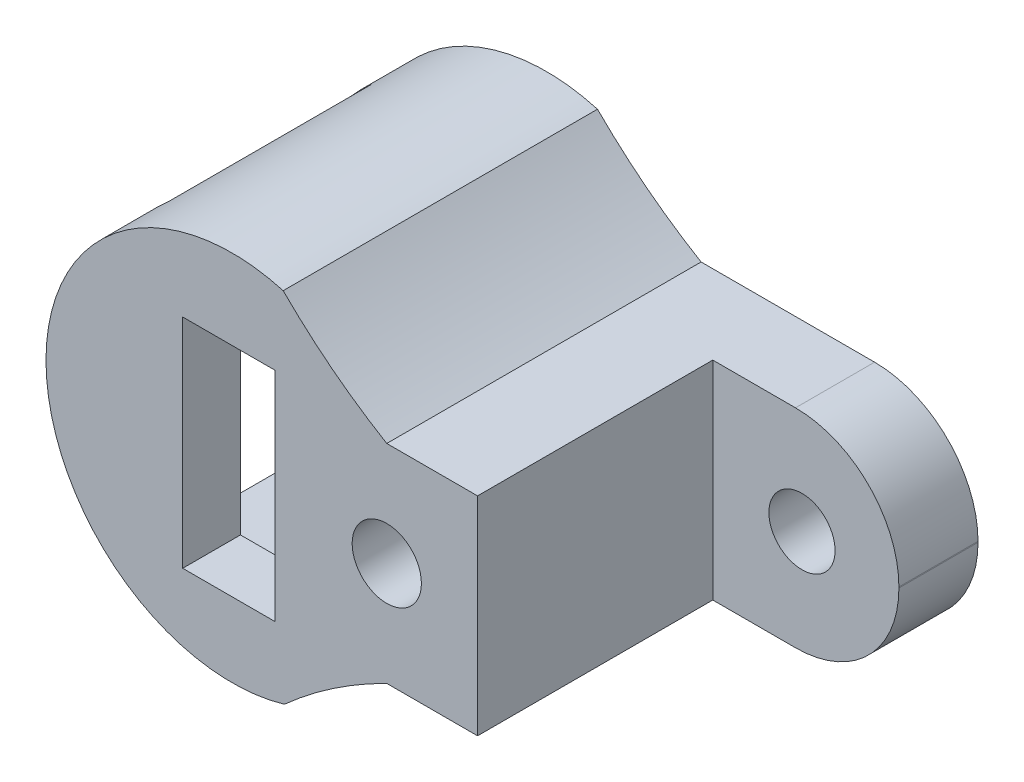
SolidWorks part; units mm, degrees
ref_plane "前视基准面" through (0, 0, 0) normal (0, 0, 1) x (1, 0, 0)
ref_plane "上视基准面" through (0, 0, 0) normal (0, 1, 0) x (1, 0, 0)
ref_plane "右视基准面" through (0, 0, 0) normal (1, 0, 0) x (0, 0, -1)
sketch "草图1" plane through (0, 0, 0) normal (0, 0, 1) x (1, 0, 0)
  line L0 (1.5398, 12.851) -> (15.553, 14.251)
  line L1 (-16.647, 18.901) -> (15.553, 18.901) construction
  line L2 (-16.647, 18.901) -> (-16.647, 12.851) construction
  line L3 (-16.647, 12.851) -> (15.553, 12.851) construction
  line L4 (15.553, 18.901) -> (15.553, 12.851) construction
  line L5 (-16.647, 18.901) -> (15.553, 12.851) construction
  line L6 (-16.647, 12.851) -> (15.553, 18.901) construction
  line L7 (14.1183, 17.876) -> (16.9877, 17.876) construction
  line L8 (14.1183, 17.876) -> (14.1183, 13.876) construction
  line L9 (14.1183, 13.876) -> (16.9877, 13.876) construction
  line L10 (16.9877, 17.876) -> (16.9877, 13.876) construction
  line L11 (14.1183, 17.876) -> (16.9877, 13.876) construction
  line L12 (14.1183, 13.876) -> (16.9877, 17.876) construction
  line L13 (15.553, 17.876) -> (1.5005, 18.901)
  line L14 (-0.547, 19.551) -> (-0.547, 12.201) construction
  line L15 (-0.547, 19.551) -> (-0.547, 20.901)
  line L16 (-0.547, 20.901) -> (19.5128, 20.901)
  line L17 (19.5128, 20.901) -> (41.453, 20.901)
  line L18 (-0.547, 12.201) -> (-0.547, 10.851)
  line L19 (-0.547, 10.851) -> (41.453, 10.851)
  line L20 (41.453, 20.901) -> (41.453, 10.851)
  line L21 (-0.547, 15.876) -> (3.9081, 15.876) construction
  circle A0 centre (-0.547, 15.876) radius 3.675 construction
  arc A1 (15.553, 14.251) -> (15.553, 17.876) centre (15.3719, 16.0635) ccw
  arc A2 (1.5398, 12.851) -> (-0.547, 12.201) centre (-0.547, 15.876) cw
  arc A3 (1.5005, 18.901) -> (-0.547, 19.551) centre (-0.547, 16.001) ccw
  point P6 (15.553, 15.876)
  dimension "D1" = 7.35
  dimension "D2" = 16.1
  dimension "D3" = 6.05
  dimension "D4" = 4
  dimension "D5" = 2
  dimension "D6" = 2
  dimension "D7" = 42
  dimension "D8" = 10.05
extrude "凸台-拉伸1" add sketch "草图1" along normal blind 2.2
sketch "草图2" plane through (0, 0, 0) normal (0, 0, -1) x (-1, 0, 0)
  line L0 (-19.5128, 10.851) -> (-49.453, 10.851)
  line L1 (-19.5128, 20.901) -> (0.547, 20.901)
  line L2 (-49.453, 10.851) -> (-49.453, 20.901)
  line L3 (-19.5128, 10.851) -> (0.547, 10.851)
  line L4 (0.547, 20.901) -> (0.547, 10.851)
  line L5 (-49.453, 20.901) -> (-19.5128, 20.901)
extrude "凸台-拉伸2" add sketch "草图2" along normal blind 3.25
sketch "草图3" plane through (0, 0, 2.2) normal (0, 0, 1) x (1, 0, 0)
  line L1 (-0.547, 20.901) -> (49.453, 20.901)
  line L3 (-0.547, 20.901) -> (-0.547, 10.851)
  line L4 (-0.547, 10.851) -> (49.453, 10.851)
  line L5 (49.453, 20.901) -> (49.453, 10.851)
extrude "凸台-拉伸3" add sketch "草图3" along normal blind 3.25
sketch "草图4" plane through (0, 0, 0) normal (0, 0, 1) x (1, 0, 0)
  line L0 (1.5005, 18.901) -> (1.5398, 12.851) construction
  line L1 (-0.547, 20.901) -> (-0.547, 10.851) construction
  line L2 (-0.547, 19.551) -> (-2.2354, 16.6161)
  line L3 (-2.2354, 16.6161) -> (-1.1109, 12.3105)
  line L4 (-1.1109, 12.3105) -> (-0.547, 12.201)
  arc A0 (1.5398, 12.851) -> (-0.547, 12.201) centre (-0.547, 15.876) cw
  arc A1 (-0.547, 19.551) -> (1.5398, 12.851) centre (-0.547, 15.876) ccw construction
  arc A2 (1.5005, 18.901) -> (-0.547, 19.551) centre (-0.547, 16.001) ccw
  arc A3 (1.5005, 18.901) -> (-0.547, 19.551) centre (-0.547, 16.001) ccw construction
  arc A4 (1.5005, 18.901) -> (1.5398, 12.851) centre (-1.5048, 15.8564) cw
extrude "切除-拉伸1" cut sketch "草图4" against normal mid plane 60
sketch "草图6" plane through (0, 0, -3.25) normal (0, 0, -1) x (-1, 0, 0)
  line L0 (-49.453, 15.876) -> (-51.7312, 15.876) construction
  line L2 (-49.453, 20.901) -> (-49.453, 10.851) construction
  circle A0 centre (-49.453, 15.876) radius 5.025
extrude "凸台-拉伸4" add sketch "草图6" against normal up to surface (8.7 mm away) up to face at (12.6389, 15.877, 5.45)
sketch "草图7" plane through (41.453, 0, 0) normal (1, 0, 0) x (0, 0, -1)
  line L0 (-1.1, 20.901) -> (-1.1, 19.7727) construction
  line L3 (-2.6, 22.1945) -> (0.4, 22.1945)
  line L4 (-2.6, 22.1945) -> (-2.6, 10.0543)
  line L5 (-2.6, 10.0543) -> (0.4, 10.0543)
  line L6 (0.4, 22.1945) -> (0.4, 10.0543)
  line L7 (-2.6, 22.1945) -> (0.4, 10.0543) construction
  line L8 (-2.6, 10.0543) -> (0.4, 22.1945) construction
  point P1 (-1.1, 16.1244)
  dimension "D1" = 3
sketch "草图8" plane through (0, 0, -3.25) normal (0, 0, -1) x (-1, 0, 0)
  line L0 (0.547, 19.551) -> (0.547, 20.901) construction
  circle A0 centre (-49.453, 15.876) radius 1.675
  circle A1 centre (-7.953, 15.8564) radius 0.84
  dimension "D1" = 3.35
  dimension "D2" = 1.68
  dimension "D3" = 8.5
extrude "切除-拉伸3" cut sketch "草图8" against normal blind 55
sketch "草图9" plane through (0, 0, -3.25) normal (0, 0, -1) x (-1, 0, 0)
  line L1 (-28.4121, 22.3056) -> (-56.8851, 22.3056)
  line L2 (-28.4121, 22.3056) -> (-28.4121, 7.7732)
  line L3 (-28.4121, 7.7732) -> (-56.8851, 7.7732)
  line L4 (-56.8851, 22.3056) -> (-56.8851, 7.7732)
extrude "切除-拉伸4" cut sketch "草图9" against normal blind 3
sketch "草图10" plane through (0, 0, 2.2) normal (0, 0, -1) x (-1, 0, 0)
  line L0 (-49.453, 20.901) -> (-38.4664, 20.901)
  line L1 (-49.453, 20.901) -> (-28.4121, 20.901) construction
  line L2 (-38.4664, 20.901) -> (-38.4664, 10.851)
  line L3 (-28.4121, 10.851) -> (-49.453, 10.851) construction
  line L4 (-38.4664, 10.851) -> (-49.453, 10.851)
  arc A0 (-49.453, 10.851) -> (-49.453, 20.901) centre (-51.7381, 15.876) ccw
extrude "凸台-拉伸5" add sketch "草图10" along normal up to surface (2.45 mm away) up to face at (51.128, 15.876, -0.25)
sketch "草图11" plane through (0, 0, -3.25) normal (0, 0, -1) x (-1, 0, 0)
  line L0 (-49.453, 20.901) -> (-28.4121, 20.901) construction
  line L1 (-38.9326, 20.901) -> (-26.3184, 20.901)
  line L2 (-38.9326, 20.901) -> (-38.9326, 10.851)
  line L3 (-38.9326, 10.851) -> (-26.3184, 10.851)
  line L4 (-26.3184, 20.901) -> (-26.3184, 10.851)
  line L5 (-28.4121, 10.851) -> (0.547, 10.851) construction
extrude "凸台-拉伸6" add sketch "草图11" against normal up to surface (3 mm away) up to face at (40.1888, 15.876, -0.25)
sketch "草图12" plane through (0, 0, -3.25) normal (0, 0, -1) x (-1, 0, 0)
  line L0 (-38.9326, 20.901) -> (-38.9326, 10.851) construction
  line L1 (-23.9326, 22.7776) -> (12.6959, 22.7776)
  line L2 (-23.9326, 22.7776) -> (-23.9326, 7.4291)
  line L3 (-23.9326, 7.4291) -> (12.6959, 7.4291)
  line L4 (12.6959, 22.7776) -> (12.6959, 7.4291)
  point P6 (-38.9326, 15.876)
  dimension "D1" = 15
extrude "切除-拉伸5" cut sketch "草图12" against normal blind 10 contours L4 L3 L2 L1
sketch "草图13" plane through (23.9326, 0, 0) normal (-1, 0, 0) x (0, 0, 1)
  line L1 (-1.575, 18.7994) -> (3.775, 18.7994)
  line L2 (-1.575, 18.7994) -> (-1.575, 13.4494)
  line L3 (-1.575, 13.4494) -> (3.775, 13.4494)
  line L4 (3.775, 18.7994) -> (3.775, 13.4494)
  line L5 (-1.575, 18.7994) -> (3.775, 13.4494) construction
  line L6 (-1.575, 13.4494) -> (3.775, 18.7994) construction
  point P0 (1.1, 16.1244)
  dimension "D1" = 5.35
  dimension "D2" = 5.35
extrude "切除-拉伸6" cut sketch "草图13" against normal blind 14
sketch "草图14" plane through (0, 20.901, 0) normal (0, 1, 0) x (1, 0, 0)
  circle A0 centre (30.5382, -1.1) radius 1.1
  dimension "D1" = 2.2
extrude "切除-拉伸7" cut sketch "草图14" against normal blind 14
sketch "草图15" plane through (0, 0, 5.45) normal (0, 0, 1) x (1, 0, 0)
  circle A0 centre (36.8799, 15.8828) radius 1.1
extrude "切除-拉伸8" cut sketch "草图15" against normal blind 10
sketch "草图16" plane through (0, 0, -0.25) normal (0, 0, -1) x (-1, 0, 0)
  line L1 (-49.453, 20.901) -> (23.547, 20.901)
  line L2 (-49.453, 20.901) -> (-49.453, 10.851)
  line L3 (-49.453, 10.851) -> (23.547, 10.851)
  circle A0 centre (23.547, 15.876) radius 5.025 construction
  arc A1 (23.547, 20.901) -> (23.547, 10.851) centre (23.547, 15.876) cw
  circle A2 centre (23.547, 15.876) radius 1.625
  dimension "D2" = 3.25
  dimension "D1" = 73
extrude "凸台-拉伸7" add sketch "草图16" against normal up to surface (5.7 mm away) up to face at (37.9799, 15.8828, 5.45)
sketch "草图17" plane through (0, 0, -3.25) normal (0, 0, -1) x (-1, 0, 0)
  line L1 (-43.1398, 23.5488) -> (-23.2167, 23.5488)
  line L2 (-43.1398, 23.5488) -> (-43.1398, 8.4657)
  line L3 (-43.1398, 8.4657) -> (-23.2167, 8.4657)
  line L4 (-23.2167, 23.5488) -> (-23.2167, 8.4657)
extrude "切除-拉伸9" cut sketch "草图17" against normal up to surface (3 mm away) up to face at (-25.172, 15.876, -0.25)
sketch "草图18" plane through (0, 0, -0.25) normal (0, 0, -1) x (-1, 0, 0)
  line L0 (-49.453, 17.551) -> (-49.453, 14.201) construction
  line L1 (-31.6616, 15.876) -> (8.461, 15.876) construction
  line L2 (-31.6616, 17.3033) -> (8.461, 17.3033)
  line L3 (-31.6616, 14.4488) -> (8.461, 14.4488)
  circle A0 centre (-49.453, 15.876) radius 1.675
  arc A1 (-31.6616, 17.3033) -> (-31.6616, 14.4488) centre (-31.6616, 15.876) ccw
  arc A2 (8.461, 14.4488) -> (8.461, 17.3033) centre (8.461, 15.876) ccw
  circle A3 centre (14.8432, 15.876) radius 1.6
  point P6 (-11.6003, 15.876)
  dimension "D1" = 3.2
extrude "切除-拉伸10" cut sketch "草图18" against normal blind 6
sketch "草图19" plane through (0, 0, -0.25) normal (0, 0, -1) x (-1, 0, 0)
  line L0 (-49.453, 20.901) -> (23.547, 20.901) construction
  line L1 (23.547, 10.851) -> (-49.453, 10.851) construction
  line L2 (12.6975, 20.901) -> (-60.9995, 39.3751)
  line L3 (-60.9995, 39.3751) -> (-58.7388, -10.2285)
  line L4 (-58.7388, -10.2285) -> (12.6975, 10.851)
  line L5 (12.6975, 20.901) -> (10.1565, 20.901)
  line L6 (10.1565, 20.901) -> (10.1565, 10.851)
  line L7 (10.1565, 10.851) -> (12.6975, 10.851)
extrude "切除-拉伸11" cut sketch "草图19" against normal blind 10
sketch "草图21" plane through (0, 0, 5.45) normal (0, 0, 1) x (1, 0, 0)
  line L0 (-23.547, 10.851) -> (-10.1565, 10.851) construction
  line L1 (-23.547, 20.901) -> (-12.6975, 20.901)
  line L2 (-12.6975, 10.851) -> (-23.547, 10.851)
  arc A0 (-23.547, 20.901) -> (-23.547, 10.851) centre (-23.547, 15.876) ccw
  arc A1 (-23.547, 20.901) -> (-23.547, 10.851) centre (-23.547, 15.876) ccw construction
  arc A2 (-12.6975, 20.901) -> (-12.6975, 10.851) centre (-15.7692, 15.876) cw
  arc A3 (-12.6975, 10.851) -> (-9.8814, 15.736) centre (-15.7692, 15.876) ccw construction
extrude "凸台-拉伸8" add sketch "草图21" along normal blind 9.5
sketch "草图22" plane through (0, 0, -0.25) normal (0, 0, -1) x (-1, 0, 0)
  line L0 (23.547, 20.901) -> (26.6011, 16.3683)
  line L1 (26.6011, 16.3683) -> (23.547, 10.851)
  arc A1 (23.547, 20.901) -> (28.5564, 24.7947) centre (10.6026, 42.7239) ccw
  arc A2 (23.547, 10.851) -> (23.547, 20.901) centre (23.547, 15.876) ccw construction
  arc A3 (23.547, 10.851) -> (28.4977, 7.5024) centre (13.8919, -8.7576) cw
  arc A4 (28.5564, 24.7947) -> (28.4977, 7.5024) centre (31.0258, 16.1401) cw
  point P0 (28.8859, 7.1508)
  dimension "D2" = 9
extrude "凸台-拉伸9" add sketch "草图22" against normal up to surface (15.2 mm away) up to face at (-18.6741, 15.876, 14.95)
sketch "草图23" plane through (-10.1565, 0, 0) normal (1, 0, 0) x (0, 0, -1)
  line L1 (-18.3686, 21.4962) -> (-3.5748, 21.4962)
  line L2 (-18.3686, 21.4962) -> (-18.3686, 9.899)
  line L3 (-18.3686, 9.899) -> (-3.5748, 9.899)
  line L4 (-3.5748, 21.4962) -> (-3.5748, 9.899)
  line L5 (-18.3686, 21.4962) -> (-3.5748, 9.899) construction
  line L6 (-18.3686, 9.899) -> (-3.5748, 21.4962) construction
  point P0 (-10.9717, 15.6976)
  point P5 (-8.5748, 15.7002)
extrude "切除-拉伸12" cut sketch "草图23" against normal mid plane 18
sketch "草图25" plane through (0, 0, -0.25) normal (0, 0, -1) x (-1, 0, 0)
  circle A0 centre (14.8432, 15.876) radius 1.6
  circle A1 centre (23.547, 15.876) radius 1.674
extrude "切除-拉伸13" cut sketch "草图25" against normal blind 20
fillet "圆角1" radius 5 2 edges at (-10.1565, 20.901, 1.6624) (-10.1565, 10.851, 1.6624)
sketch "草图26" plane through (0, 0, -0.25) normal (0, 0, -1) x (-1, 0, 0)
  line L0 (40.0257, 16.1095) -> (37.0571, 16.1095) construction
  line L1 (40.0257, 16.1095) -> (40.0257, 11.3276) construction
  line L3 (40.0257, 24.2447) -> (40.9515, 24.2447)
  line L4 (40.0257, 24.2447) -> (40.0257, 7.973)
  line L5 (40.0257, 7.973) -> (40.9515, 7.973)
  line L6 (40.9515, 24.2447) -> (40.9515, 7.973)
extrude "凸台-拉伸10" add sketch "草图26" against normal blind 15
sketch "草图27" plane through (-40.9515, 0, 0) normal (-1, 0, 0) x (0, 0, 1)
  line L0 (2.3572, 22.9783) -> (12.1572, 9.1783) construction
  line L1 (2.3572, 22.9783) -> (12.1572, 22.9783)
  line L2 (2.3572, 22.9783) -> (2.3572, 9.1783)
  line L3 (2.3572, 9.1783) -> (12.1572, 9.1783)
  line L4 (12.1572, 22.9783) -> (12.1572, 9.1783)
  line L5 (2.3572, 9.1783) -> (12.1572, 22.9783) construction
  dimension "D1" = 13.8
  dimension "D2" = 9.8
extrude "切除-拉伸14" cut sketch "草图27" against normal blind 12
sketch "草图28" plane through (0, 0, 12.1572) normal (0, 0, -1) x (-1, 0, 0)
  line L1 (28.9538, 21.264) -> (33.4147, 21.264)
  line L2 (28.9538, 21.264) -> (28.9538, 10.7396)
  line L3 (28.9538, 10.7396) -> (33.4147, 10.7396)
  line L4 (33.4147, 21.264) -> (33.4147, 10.7396)
extrude "切除-拉伸15" cut sketch "草图28" against normal blind 12
sketch "草图29" plane through (0, 0, -0.25) normal (0, 0, -1) x (-1, 0, 0)
  line L0 (40.9515, 7.973) -> (40.9515, 24.2447) construction
  line L1 (40.0257, 24.2447) -> (40.9515, 24.2447)
  line L2 (40.0257, 24.2447) -> (40.0257, 7.973)
  line L3 (40.0257, 7.973) -> (40.9515, 7.973)
  line L4 (40.9515, 24.2447) -> (40.9515, 7.973)
  line L5 (40.0257, 7.973) -> (40.9515, 7.973) construction
extrude "切除-拉伸16" cut sketch "草图29" against normal blind 18
sketch "草图30" plane through (-28.9515, 0, 0) normal (-1, 0, 0) x (0, 0, 1)
  line L0 (2.3572, 9.1783) -> (12.1572, 9.1783) construction
  line L1 (2.3572, 22.9783) -> (3.8572, 22.9783)
  line L2 (2.3572, 22.9783) -> (2.3572, 9.1783)
  line L3 (2.3572, 9.1783) -> (3.8572, 9.1783)
  line L4 (3.8572, 22.9783) -> (3.8572, 9.1783)
  dimension "D1" = 1.5
extrude "凸台-拉伸11" add sketch "草图30" along normal blind 3.25
